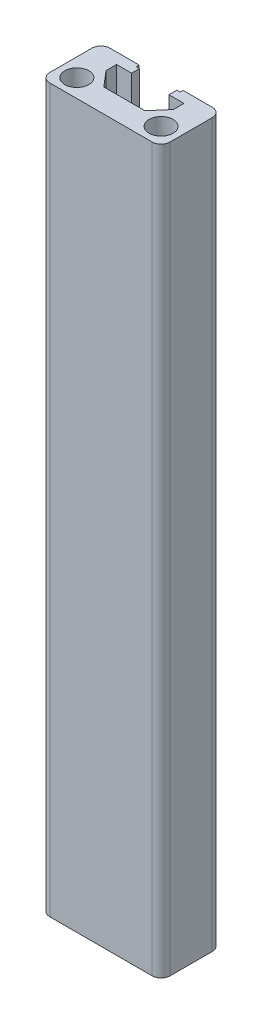
SolidWorks part; units mm, degrees
ref_plane "前视基准面" through (0, 0, 0) normal (0, 0, 1) x (1, 0, 0)
ref_plane "上视基准面" through (0, 0, 0) normal (0, 1, 0) x (1, 0, 0)
ref_plane "右视基准面" through (0, 0, 0) normal (1, 0, 0) x (0, 0, -1)
sketch "草图1" plane through (0, 0, 0) normal (0, 1, 0) x (1, 0, 0)
  line L0 (0, 0) -> (20, 0)
  line L1 (20, 0) -> (20, 10)
  line L2 (20, 10) -> (13.65, 10)
  line L3 (0, 10) -> (0, 0)
  line L4 (6.35, 10) -> (6.35, 9.5104)
  line L5 (6.35, 9.5104) -> (6.9, 9.5104)
  line L6 (6.9, 9.5104) -> (6.9, 8.2)
  line L7 (6.9, 8.2) -> (4.4, 8.2)
  line L8 (4.4, 8.2) -> (4.4, 6.4475)
  line L9 (4.4, 6.4475) -> (6.5873, 3.9)
  line L11 (15.6, 6.4475) -> (15.6, 8.2)
  line L12 (15.6, 8.2) -> (13.1, 8.2)
  line L13 (13.1, 8.2) -> (13.1, 9.5104)
  line L14 (13.1, 9.5104) -> (13.65, 9.5104)
  line L15 (13.65, 9.5104) -> (13.65, 10)
  line L16 (6.35, 10) -> (0, 10)
  line L17 (10, 0) -> (10, 13.7687) construction
  line L18 (6.5873, 3.9) -> (13.4127, 3.9)
  line L19 (13.4127, 3.9) -> (15.6, 6.4475)
  circle A0 centre (3, 3) radius 2
  circle A1 centre (17, 3) radius 2
  point P12 (10, 3.9)
  dimension "D8" = 4
  dimension "D1" = 20
  dimension "D2" = 10
  dimension "D3" = 7.3
  dimension "D4" = 6.2
  dimension "D5" = 1.8
  dimension "D6" = 4.3
  dimension "D7" = 11.2
  dimension "D9" = 3
  dimension "D10" = 14
extrude "凸台-拉伸1" add sketch "草图1" along normal blind 120
fillet "圆角1" radius 1.5 4 edges at (0, 60, -10) (0, 60, 0) (20, 60, -10) (20, 60, 0)
